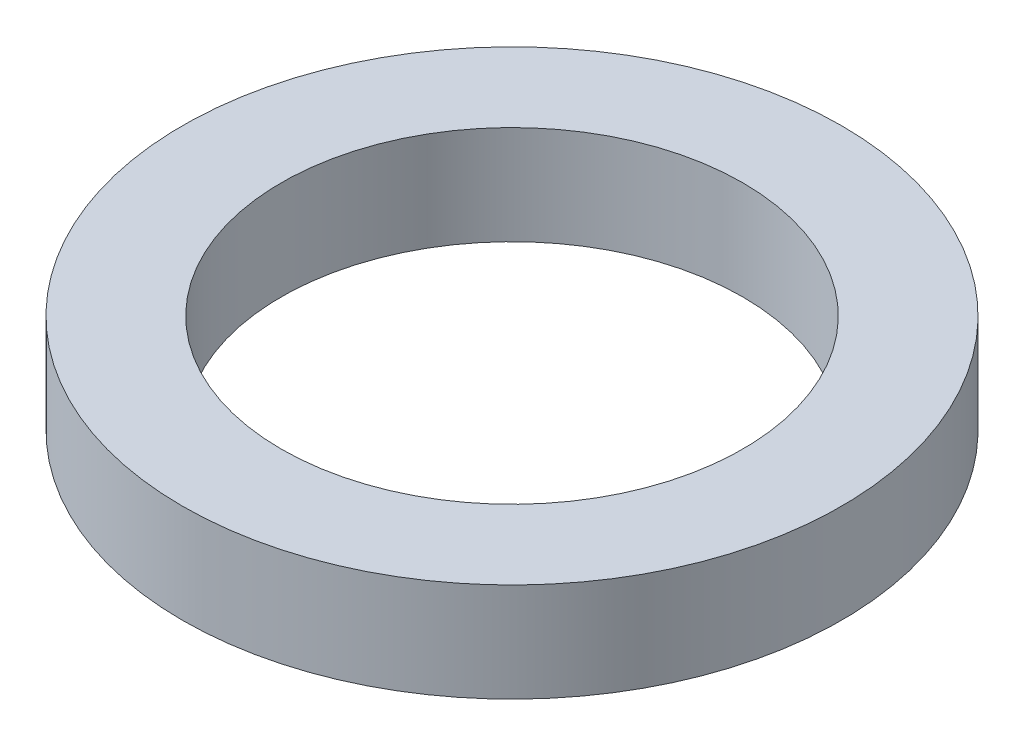
SolidWorks part; units mm, degrees
ref_plane "Front Plane" through (0, 0, 0) normal (0, 0, 1) x (1, 0, 0)
ref_plane "Top Plane" through (0, 0, 0) normal (0, 1, 0) x (1, 0, 0)
ref_plane "Right Plane" through (0, 0, 0) normal (1, 0, 0) x (0, 0, -1)
sketch "Sketch1" plane through (0, 0, 0) normal (0, 1, 0) x (1, 0, 0)
  circle A0 centre (0, 0) radius 5
  circle A1 centre (0, 0) radius 3.5005
  dimension "D1" = 7.001
  dimension "D2" = 10
extrude "Boss-Extrude1" add sketch "Sketch1" along normal blind 1.5
